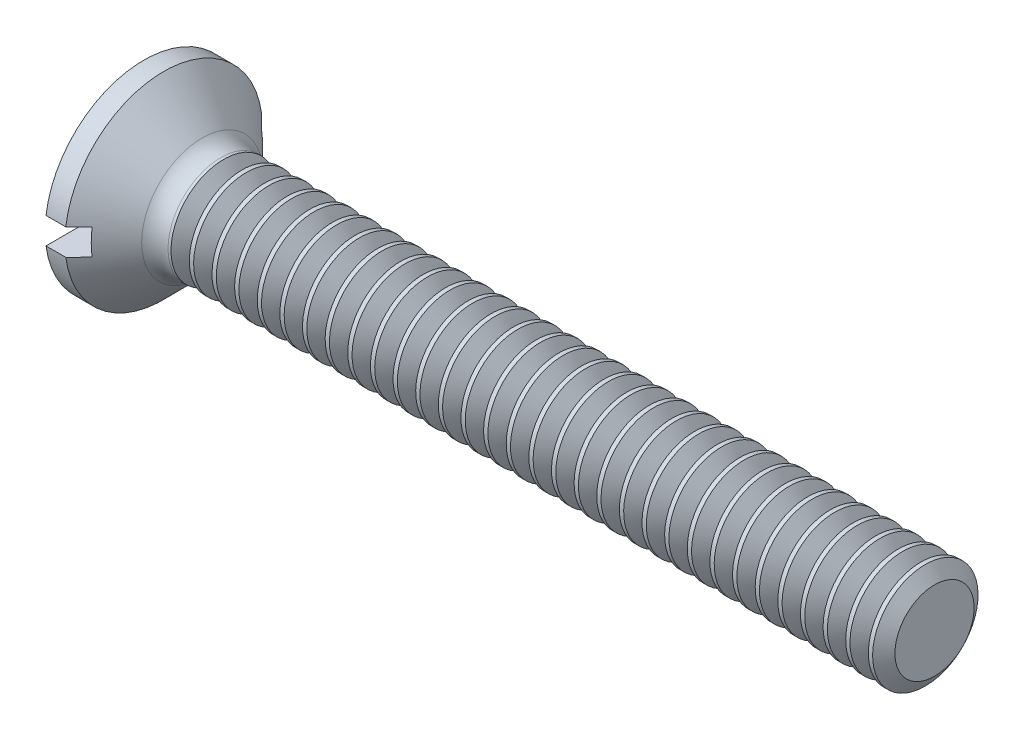
SolidWorks part; units mm, degrees
ref_plane "Plane1" through (0, 0, 0) normal (0, 0, 1) x (1, 0, 0)
ref_plane "Plane2" through (0, 0, 0) normal (0, 1, 0) x (1, 0, 0)
ref_plane "Plane3" through (0, 0, 0) normal (1, 0, 0) x (0, 0, -1)
sketch "BodySke" plane through (0, 0, 0) normal (0, 0, 1) x (1, 0, 0)
  line L0 (0, 0) -> (0, 1.5)
  line L1 (0, 1.5) -> (0.3, 1.5)
  line L2 (1, 0.8) -> (12, 0.8)
  line L3 (12, 0.8) -> (12, 0)
  line L4 (12, 0) -> (0, 0)
  line L5 (-6.35, 0) -> (82.55, 0) construction
  line L6 (1, -0.8) -> (12, -0.8) construction
  line L7 (0.3, -1.5) -> (1, -0.8) construction
  line L8 (0.3, 1.5) -> (1, 0.8)
  line L9 (0, -1.5) -> (0.3, -1.5) construction
  line L10 (1.35, 2.3875) -> (1.35, -7.1375) construction
  line L11 (0, 6.35) -> (0, -3.175) construction
  dimension "Diameter" = 1.6
  dimension "Length" = 12
  dimension "Head_ht" = 1
  dimension "Head_dia" = 3
  dimension "Head_ang" = 90
  dimension "D6" = 0.3
  dimension "Advance" = 0.35
  dimension "Thread_nom" = 12
revolve "Base-Revolve" add sketch "BodySke" angle 360 about L5
cosmetic thread "ThreadCosmetic" [suppressed] parameters "Thread_length"=10.65, "Thread_minor"=1.202
fillet "Fillet1" radius 0.4 1 edges at (1, 0, 0.8)
sketch "Sketch2" plane through (0, 0, 0) normal (-1, 0, 0) x (0, 0, 1)
  line L0 (-1.5, -0.2) -> (1.5, -0.2)
  line L1 (-1.5, -0.2) -> (-1.5, 0.2)
  line L2 (1.5, 0.2) -> (-1.5, 0.2)
  line L3 (1.5, 0.2) -> (1.5, -0.2)
  dimension "D1" = 0.2
  dimension "Slot_width" = 0.4
  dimension "D2" = 3
  dimension "D3" = 1.5
extrude "Slot" cut sketch "Sketch2" against normal blind 0.5
sketch "ThdSchSke" plane through (0, 0, 0) normal (0, 0, 1) x (1, 0, 0)
  line L0 (1.35, -0.601) -> (1.2107, -0.8)
  line L1 (1.35, -0.601) -> (1.4893, -0.8)
  line L2 (1.4893, -0.8) -> (1.4893, -1)
  line L3 (-3.175, 0) -> (5.1513, 0) construction
  line L5 (1.4893, -1) -> (1.2107, -1)
  line L6 (1.2107, -1) -> (1.2107, -0.8)
  line L7 (0, 1.5) -> (0, 0.2) construction
  dimension "Thread_minor" = 1.202
  dimension "Diameter" = 1.6
  dimension "Start" = 1.35
  dimension "SideAngle" = 55
  dimension "VeeAngle" = 70
  dimension "Overcut" = 2
revolve "ThreadSchematic" cut sketch "ThdSchSke" angle 360 about L3
pattern_linear "ThdSchPat" count 32 spacing 0.3435 along (1, 0, 0) of "ThreadSchematic"
equation "\"D1@Sketch2\" = \"Slot_width@Sketch2\" / 2"
equation "\"D2@Sketch2\" = \"Head_dia@BodySke\""
equation "\"D3@Sketch2\" = \"D2@Sketch2\" / 2"
equation "\"Thread_length@ThreadCosmetic\" = ((sgn( (\"Length@BodySke\" - \"Advance@BodySke\" * 1.0 - \"Head_ht@BodySke\" ) - \"Thread_nom@BodySke\" )-1)*( (\"Length@BodySke\" - \"Advance@BodySke\" * 1.0 - \"Head_ht@BodySke\" ) - \"Thread_nom@BodySke\" ))/-2+ \"Thread_nom@BodySke\""
equation "\"Thread_minor@ThdSchSke\" = \"Thread_minor@ThreadCosmetic\""
equation "\"Diameter@ThdSchSke\" = \"Diameter@BodySke\""
equation "\"Overcut@ThdSchSke\" = \"Diameter@BodySke\" * 1.25"
equation "\"Start@ThdSchSke\" = 0.000001 + \"Length@BodySke\" - \"Thread_length@ThreadCosmetic\"  '---Countersunk---"
equation "\"Num_threads@ThdSchPat\" = int( \"Thread_length@ThreadCosmetic\" / \"Advance@BodySke\" + 0.999 )  + 1"
equation "\"Advance@ThdSchPat\" = \"Thread_length@ThreadCosmetic\" /  (\"Num_threads@ThdSchPat\" - 1) 'relax it"
